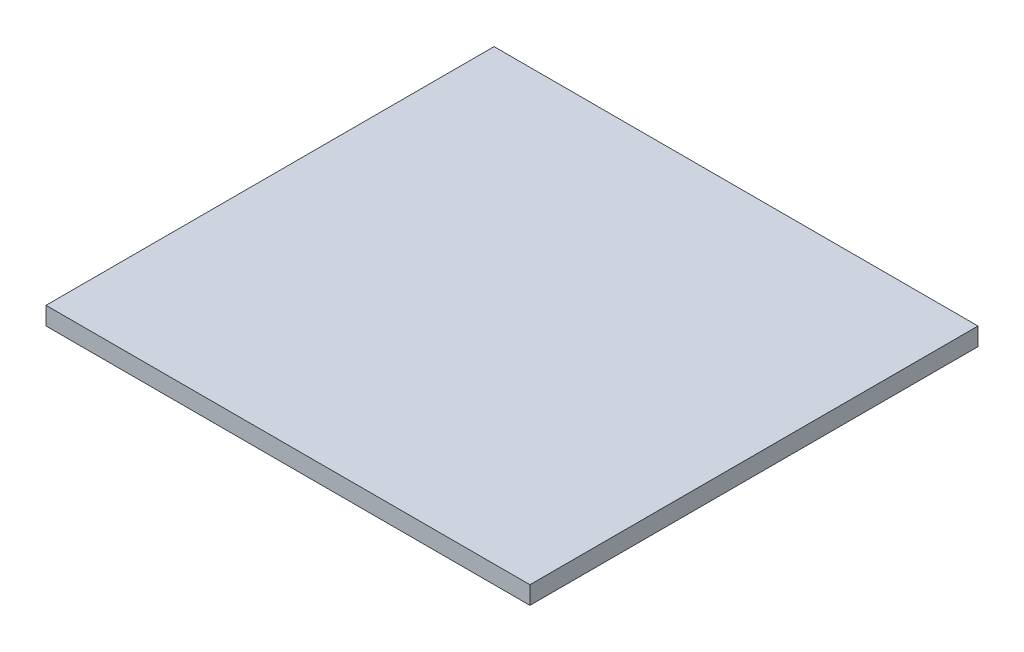
SolidWorks part; units mm, degrees
ref_plane "Front Plane" through (0, 0, 0) normal (0, 0, 1) x (1, 0, 0)
ref_plane "Top Plane" through (0, 0, 0) normal (0, 1, 0) x (1, 0, 0)
ref_plane "Right Plane" through (0, 0, 0) normal (1, 0, 0) x (0, 0, -1)
sketch "Sketch1" plane through (0, 0, 0) normal (0, 1, 0) x (1, 0, 0)
  line L1 (0, 0) -> (54, 0)
  line L2 (0, 0) -> (0, 50)
  line L3 (0, 50) -> (54, 50)
  line L4 (54, 0) -> (54, 50)
  dimension "D1" = 54
  dimension "D2" = 50
extrude "Boss-Extrude1" add sketch "Sketch1" along normal blind 2
